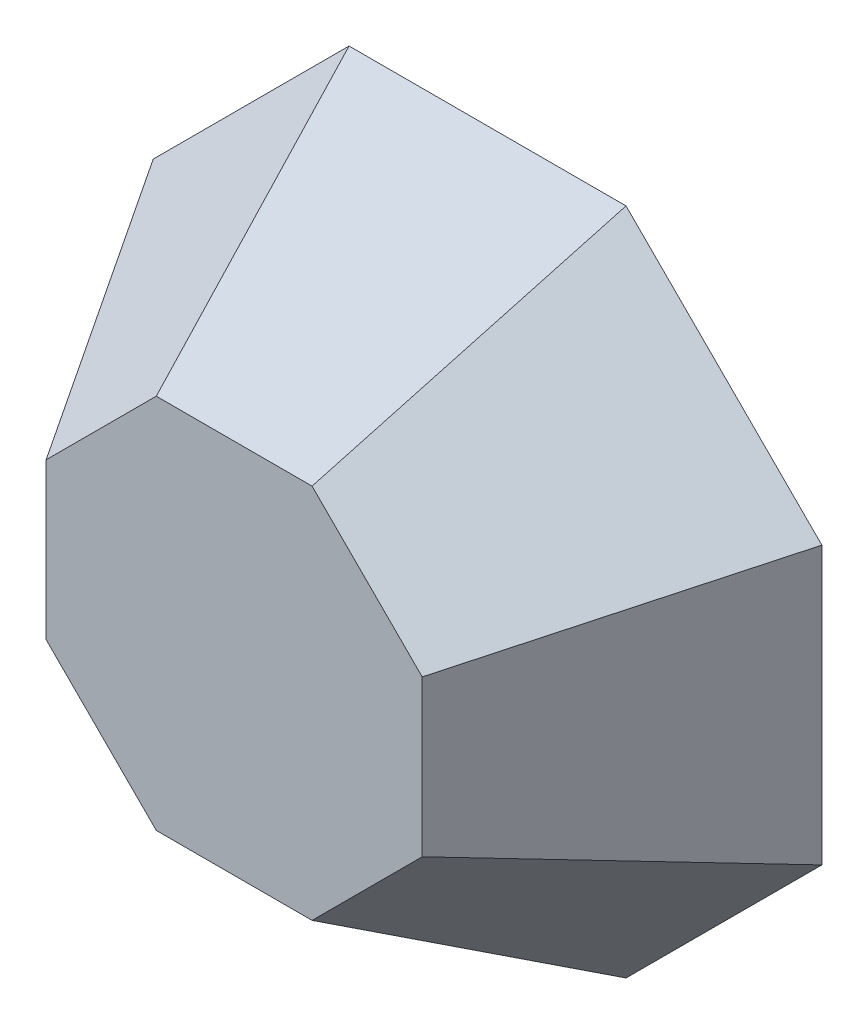
SolidWorks part; units mm, degrees
ref_plane "Plano frontal" through (0, 0, 0) normal (0, 0, 1) x (1, 0, 0)
ref_plane "Plano superior" through (0, 0, 0) normal (0, 1, 0) x (1, 0, 0)
ref_plane "Plano direito" through (0, 0, 0) normal (1, 0, 0) x (0, 0, -1)
sketch "Esboço1" plane through (0, 0, 0) normal (0, 0, 1) x (1, 0, 0)
  line L1 (52.78, -21.8622) -> (52.78, 21.8622)
  line L2 (52.78, 21.8622) -> (21.8622, 52.78)
  line L3 (21.8622, 52.78) -> (-21.8622, 52.78)
  line L4 (-21.8622, 52.78) -> (-52.78, 21.8622)
  line L5 (-52.78, 21.8622) -> (-52.78, -21.8622)
  line L6 (-52.78, -21.8622) -> (-21.8622, -52.78)
  line L7 (-21.8622, -52.78) -> (21.8622, -52.78)
  line L8 (21.8622, -52.78) -> (52.78, -21.8622)
  circle A0 centre (0, 0) radius 52.78 construction
  circle A1 centre (0, 0) radius 50.78 construction
  dimension "D1" = 105.56
  dimension "D2" = 2
extrude "Ressalto-extrusão1" add sketch "Esboço1" along normal blind 40 draft 30
